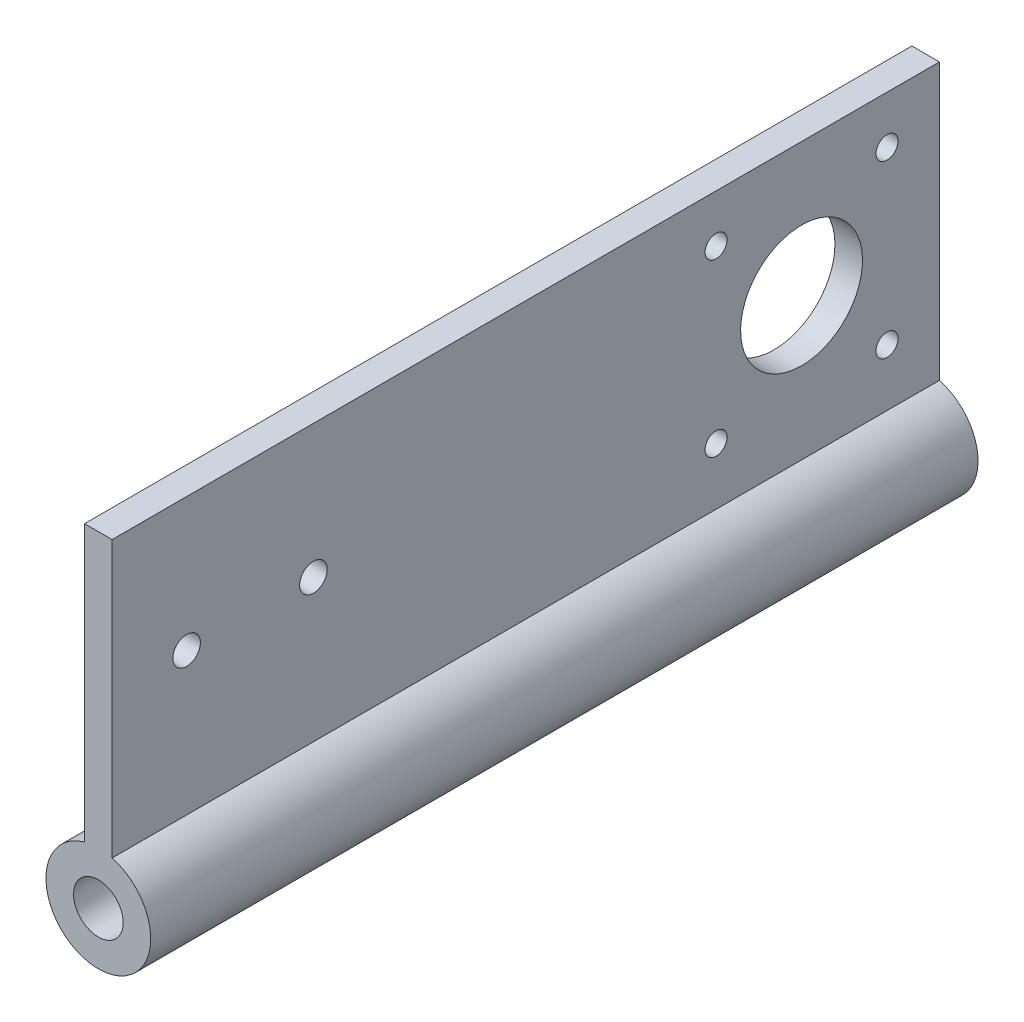
SolidWorks part; units mm, degrees
ref_plane "Front Plane" through (0, 0, 0) normal (0, 0, 1) x (1, 0, 0)
ref_plane "Top Plane" through (0, 0, 0) normal (0, 1, 0) x (1, 0, 0)
ref_plane "Right Plane" through (0, 0, 0) normal (1, 0, 0) x (0, 0, -1)
sketch "Sketch1" plane through (0, 0, 0) normal (0, 0, 1) x (1, 0, 0)
  line L0 (-2.5, 59.1652) -> (-2.5, 9.1652)
  line L1 (2.5, 59.1652) -> (2.5, 9.1652)
  line L2 (-2.5, 59.1652) -> (2.5, 59.1652)
  circle A0 centre (0, 0) radius 4.5
  arc A1 (-2.5, 9.1652) -> (2.5, 9.1652) centre (0, 0) ccw
  dimension "D1" = 9
  dimension "D2" = 5
  dimension "D3" = 5
  dimension "D4" = 50
extrude "Boss-Extrude1" add sketch "Sketch1" along normal blind 150
sketch "Sketch2" plane through (-2.5, 0, 0) normal (-1, 0, 0) x (0, 0, 1)
  line L0 (9.5, 19.5) -> (40.5, 50.5) construction
  line L5 (0, 59.1652) -> (0, 9.1652) construction
  circle A0 centre (9.5, 50.5) radius 2
  circle A1 centre (40.5, 50.5) radius 2
  circle A2 centre (40.5, 19.5) radius 2
  circle A3 centre (9.5, 19.5) radius 2
  circle A4 centre (25, 35) radius 11.05
  dimension "D2" = 31
  dimension "D3" = 4
  dimension "D4" = 22.1
  dimension "D5" = 25
  dimension "D6" = 35
  dimension "D1" = 31
extrude "Cut-Extrude1" cut sketch "Sketch2" against normal through all
sketch "Sketch3" plane through (-2.5, 0, 0) normal (-1, 0, 0) x (0, 0, 1)
  line L3 (113.5, 35) -> (136.5, 35) construction
  line L4 (150, 59.1652) -> (150, 9.1652) construction
  circle A0 centre (113.5, 35) radius 2.5
  circle A1 centre (136.5, 35) radius 2.5
  point P4 (125, 35)
  point P9 (136.5, 35)
  dimension "D1" = 23
  dimension "D2" = 5
  dimension "D3" = 25
  dimension "D4" = 35
extrude "Cut-Extrude2" cut sketch "Sketch3" against normal through all
